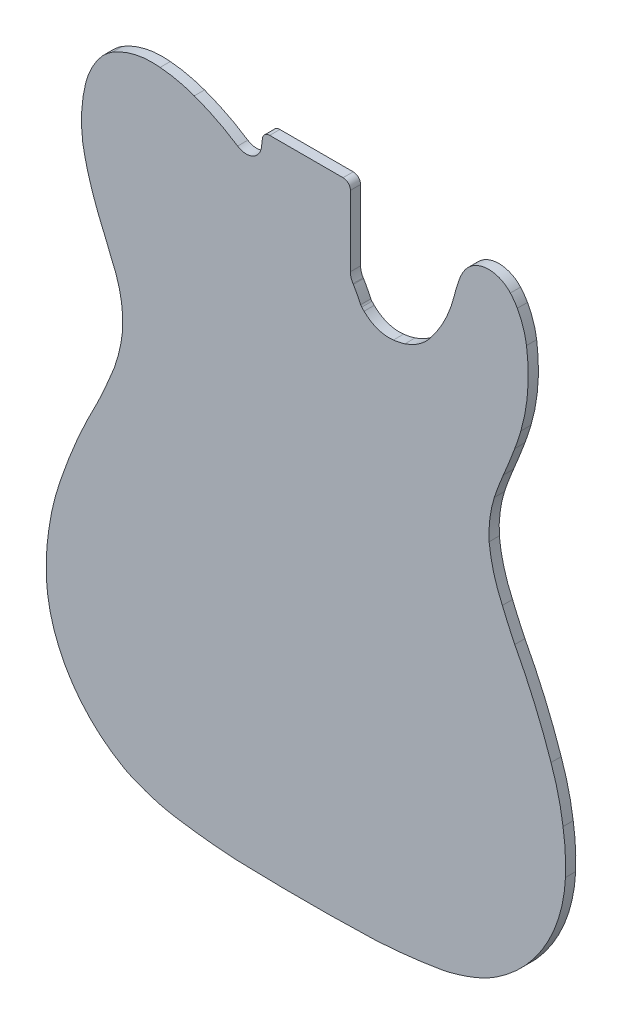
SolidWorks part; units mm, degrees
ref_plane "Front Plane" through (0, 0, 0) normal (0, 0, 1) x (1, 0, 0)
ref_plane "Top Plane" through (0, 0, 0) normal (0, 1, 0) x (1, 0, 0)
ref_plane "Right Plane" through (0, 0, 0) normal (1, 0, 0) x (0, 0, -1)
sketch "Sketch1" plane through (0, 0, 0) normal (0, 0, 1) x (1, 0, 0)
  line L0 (255.3675, -212.0656) -> (264.4462, -212.0656) construction
  line L1 (264.4462, -212.0656) -> (273.5248, -212.0656) construction
  line L2 (254.4921, -211.9425) -> (229.09, -204.656) construction
  line L3 (274.4003, -211.9425) -> (299.8024, -204.656) construction
  line L4 (264.4462, -197.0288) -> (264.4462, -188.6259) construction
  line L5 (292.1992, -149.0184) -> (292.1992, -105.0808)
  line L6 (353.0408, -434.0524) -> (359.3908, -434.0524) construction
  line L7 (354.3108, -292.5744) -> (358.1208, -292.5744) construction
  line L8 (368.9158, -303.3694) -> (368.9158, -424.5274) construction
  line L9 (343.5158, -303.3694) -> (343.5158, -424.5274) construction
  line L10 (231.3871, -188.3166) -> (257.385, -188.3166) construction
  line L11 (271.5074, -188.3166) -> (297.5053, -188.3166) construction
  line L12 (292.2083, -154.6088) -> (292.4425, -170.3149) construction
  line L13 (237.3236, -111.7284) -> (236.4498, -170.3149) construction
  line L14 (261.2712, -222.8223) -> (261.2712, -212.0656) construction
  line L15 (267.6212, -222.5163) -> (267.6212, -212.0656) construction
  line L16 (355.5808, -417.0887) -> (440.1841, -462.3756)
  line L17 (170.139, -116.9111) -> (172.2398, -80.4263) construction
  line L26 (233.0908, -326.0407) -> (228.0254, -311.007) construction
  line L27 (280.249, -340.996) -> (237.8411, -330.4226) construction
  line L28 (286.5004, -339.3572) -> (298.0308, -328.4613) construction
  line L29 (271.5011, -294.9508) -> (296.5271, -311.3952) construction
  line L30 (267.182, -293.874) -> (237.3652, -296.6444) construction
  line L31 (292.2083, -154.6088) -> (293.7952, -154.6089)
  line L32 (237.3236, -111.7284) -> (236.159, -111.7284)
  line L33 (264.4462, -533.3397) -> (264.4462, -35.9424) construction
  line L34 (264.446, -176.7596) -> (264.446, -168.3324) construction
  line L35 (242.7991, -176.7596) -> (257.385, -176.7596) construction
  line L36 (271.5074, -176.7596) -> (286.0933, -176.7596) construction
  line L37 (271.5074, -188.3166) -> (271.5074, -176.7596) construction
  line L38 (257.385, -188.3166) -> (257.385, -176.7596) construction
  line L39 (311.5028, -266.3979) -> (268.9363, -223.8315) construction
  line L40 (302.5225, -275.3781) -> (259.9561, -232.8117) construction
  line L41 (287.6272, -100.5088) -> (241.8598, -100.5088)
  line L42 (236.7013, -109.5293) -> (237.3226, -104.5183)
  line L45 (368.9158, -411.6223) -> (420.0889, -439.0145)
  line L46 (362.6504, -433.4773) -> (409.7247, -458.6755)
  line L47 (300.9797, -323.698) -> (343.5158, -323.698) construction
  line L48 (300.9797, -317.348) -> (343.5158, -317.348) construction
  line L49 (343.5158, -311.8813) -> (308.6561, -277.0216) construction
  line L50 (343.5158, -302.901) -> (313.1462, -272.5315) construction
  arc A0 (298.5861, -163.6364) -> (299.2711, -164.6283) centre (301.4937, -162.3609) ccw
  arc A1 (300.7364, -166.0922) -> (299.2711, -164.6283) centre (222.8934, -242.5472) ccw
  arc A2 (300.7364, -166.0922) -> (319.0259, -172.5122) centre (316.4123, -150.6962) ccw
  arc A3 (319.0259, -172.5122) -> (326.2352, -170.944) centre (314.4164, -133.9661) ccw
  arc A4 (326.2352, -170.944) -> (341.6924, -160.3725) centre (316.2829, -139.806) ccw
  arc A5 (341.6924, -160.3725) -> (356.9315, -129.8398) centre (280.2373, -110.6305) ccw
  arc A6 (360.2177, -118.9602) -> (356.9315, -129.8398) centre (472.2447, -158.7341) ccw
  arc A7 (363.6913, -112.2691) -> (360.2177, -118.9602) centre (386.4375, -128.3247) ccw
  arc A8 (392.0008, -110.6336) -> (363.6913, -112.2691) centre (378.4982, -122.7399) ccw
  arc A9 (396.3203, -116.7099) -> (392.0008, -110.6336) centre (367.666, -132.5065) ccw
  arc A10 (402.0691, -133.9701) -> (396.3203, -116.7099) centre (352.5181, -140.8862) ccw
  arc A11 (398.5108, -181.9349) -> (402.0691, -133.9701) centre (289.2584, -149.7157) ccw
  arc A12 (394.7117, -193.3187) -> (398.5108, -181.9349) centre (237.0194, -134.3662) ccw
  arc A13 (387.6043, -211.1738) -> (394.7117, -193.3187) centre (-23.048, -37.3677) ccw
  arc A14 (387.6043, -211.1738) -> (381.9731, -226.053) centre (577.8696, -291.6876) ccw
  circle A15 centre (378.0352, -293.8788) radius 0.889
  arc A33 (368.9158, -303.3694) -> (358.1208, -292.5744) centre (358.1208, -303.3694) ccw construction
  arc A34 (354.3108, -292.5744) -> (343.5158, -303.3694) centre (354.3108, -303.3694) ccw construction
  arc A35 (231.3871, -188.3166) -> (229.09, -204.656) centre (231.3871, -196.6478) ccw construction
  arc A36 (299.8024, -204.656) -> (297.5053, -188.3166) centre (297.5053, -196.6478) ccw construction
  arc A37 (273.5248, -212.0656) -> (274.4003, -211.9425) centre (273.5248, -208.8906) ccw construction
  arc A38 (254.4921, -211.9425) -> (255.3675, -212.0656) centre (255.3675, -208.8906) ccw construction
  circle A39 centre (300.6412, -197.0288) radius 2.3813 construction
  circle A40 centre (228.2512, -197.0288) radius 2.3813 construction
  circle A41 centre (190.7346, -293.8788) radius 0.889
  circle A45 centre (216.6438, -195.7754) radius 0.9906 construction
  circle A46 centre (237.8426, -363.958) radius 0.9906 construction
  arc A47 (369.9797, -491.4239) -> (383.1407, -484.5884) centre (341.6053, -420.7038) ccw
  arc A48 (383.1407, -484.5884) -> (426.3677, -409.2054) centre (331.2197, -404.73) ccw
  circle A49 centre (361.0363, -437.4278) radius 0.9906 construction
  circle A50 centre (375.8404, -153.7439) radius 0.9906
  arc A51 (292.1992, -105.0808) -> (287.6272, -100.5088) centre (287.6272, -105.0808) ccw
  arc A52 (359.3908, -434.0524) -> (368.9158, -424.5274) centre (359.3908, -424.5274) ccw construction
  arc A53 (343.5158, -424.5274) -> (353.0408, -434.0524) centre (353.0408, -424.5274) ccw construction
  circle A55 centre (356.2158, -289.002) radius 0.8255 construction
  circle A56 centre (356.2158, -437.6248) radius 0.8255 construction
  circle A57 centre (264.4462, -249.0804) radius 1.5875 construction
  circle A58 centre (264.4462, -477.6804) radius 1.5875
  arc A59 (286.0933, -176.7596) -> (292.4425, -170.3149) centre (286.0933, -170.4096) ccw construction
  arc A60 (236.4498, -170.3149) -> (242.7991, -176.7596) centre (242.7991, -170.4096) ccw construction
  circle A61 centre (296.8434, -363.9576) radius 1.0795 construction
  circle A62 centre (275.2536, -363.9576) radius 1.0795 construction
  circle A63 centre (253.664, -363.9576) radius 1.0795 construction
  circle A64 centre (232.0734, -363.9576) radius 1.0795 construction
  circle A65 centre (291.4462, -372.0852) radius 1.651 construction
  circle A66 centre (280.6516, -372.0852) radius 1.651 construction
  circle A67 centre (269.8566, -372.0852) radius 1.651 construction
  circle A68 centre (259.061, -372.0852) radius 1.651 construction
  circle A69 centre (248.2654, -372.0852) radius 1.651 construction
  circle A70 centre (237.4714, -372.0852) radius 1.651 construction
  circle A91 centre (378.3902, -122.9872) radius 0.889
  circle A92 centre (324.0598, -293.8788) radius 0.889 construction
  circle A93 centre (228.8868, -140.5904) radius 0.889
  arc A94 (237.3652, -296.6444) -> (228.0254, -311.007) centre (238.3756, -307.5196) ccw construction
  arc A95 (233.0908, -326.0407) -> (237.8411, -330.4226) centre (239.4695, -323.8915) ccw construction
  arc A96 (280.249, -340.996) -> (286.5004, -339.3572) centre (281.8774, -334.465) ccw construction
  arc A97 (298.0308, -328.4613) -> (296.5271, -311.3952) centre (290.5293, -320.523) ccw construction
  arc A98 (271.5011, -294.9508) -> (267.182, -293.874) centre (267.8047, -300.5761) ccw construction
  arc A99 (268.9363, -223.8315) -> (259.9561, -232.8117) centre (264.4462, -228.3216) ccw construction
  arc A100 (302.5225, -275.3781) -> (311.5028, -275.3781) centre (307.0126, -270.888) ccw construction
  arc A101 (311.5028, -275.3781) -> (311.5028, -266.3979) centre (307.0126, -270.888) ccw construction
  circle A102 centre (245.3978, -160.8336) radius 2.032
  circle A103 centre (283.4978, -160.8336) radius 2.032
  circle A104 centre (283.4978, -110.0336) radius 2.032
  circle A105 centre (245.3978, -110.0336) radius 2.032
  arc A106 (241.8598, -100.5088) -> (237.3226, -104.5183) centre (241.8598, -105.0808) ccw
  arc A107 (292.1992, -149.0184) -> (293.7952, -154.6089) centre (302.5829, -149.077) ccw
  arc A108 (293.7952, -154.6089) -> (294.036, -154.9688) centre (302.7937, -148.8489) ccw
  arc A109 (298.5861, -163.6364) -> (294.036, -154.9688) centre (234.5218, -191.7393) ccw
  arc A110 (381.9731, -226.053) -> (378.7456, -251.638) centre (451.614, -247.8341) ccw
  arc A111 (378.7456, -251.638) -> (387.0056, -281.868) centre (473.536, -241.9811) ccw
  arc A112 (387.0056, -281.868) -> (394.746, -299.1376) centre (668.7935, -165.937) ccw
  arc A113 (417.3556, -351.5884) -> (394.746, -299.1376) centre (80.4909, -465.6996) ccw
  arc A114 (424.8464, -382.4484) -> (417.3556, -351.5884) centre (273.7558, -402.7844) ccw
  arc A115 (426.3677, -409.2054) -> (424.8464, -382.4484) centre (286.7086, -403.7238) ccw
  arc A116 (353.3461, -496.801) -> (369.9797, -491.4239) centre (322.6987, -373.581) ccw
  arc A117 (307.8756, -502.3376) -> (349.8373, -497.5433) centre (288.5477, -147.1431) ccw
  arc A118 (221.4182, -502.3513) -> (307.8756, -502.3376) centre (264.4456, 766.9622) ccw
  arc A119 (182.0911, -498.0608) -> (220.5936, -502.3144) centre (240.3434, -147.16) ccw
  arc A120 (155.5294, -490.0098) -> (168.8471, -494.9386) centre (206.2073, -373.5338) ccw
  arc A121 (102.5148, -408.988) -> (150.7976, -487.651) centre (197.6727, -404.73) ccw
  arc A122 (104.046, -382.4484) -> (102.5148, -408.988) centre (242.065, -403.7256) ccw
  arc A123 (111.5356, -351.5884) -> (104.046, -382.4484) centre (255.1378, -402.7788) ccw
  arc A124 (134.1464, -299.1376) -> (111.5356, -351.5884) centre (448.2456, -465.6404) ccw
  arc A125 (134.1464, -299.1376) -> (141.8856, -281.868) centre (-139.905, -165.9555) ccw
  arc A126 (141.8856, -281.868) -> (150.1456, -251.638) centre (55.4068, -241.9953) ccw
  arc A127 (150.1456, -251.638) -> (143.0364, -216.2088) centre (77.3673, -247.8137) ccw
  arc A128 (143.0364, -216.2088) -> (136.806, -200.9676) centre (-189.4378, -343.226) ccw
  arc A129 (129.8252, -181.788) -> (136.806, -200.9676) centre (324.3166, -121.8593) ccw
  arc A130 (125.2556, -162.9888) -> (129.8252, -181.788) centre (275.6939, -136.3761) ccw
  arc A131 (127.036, -129.7188) -> (125.2556, -162.9888) centre (213.3553, -151.0206) ccw
  arc A132 (137.4456, -109.7788) -> (127.036, -129.7188) centre (173.1607, -141.1109) ccw
  arc A133 (143.666, -104.698) -> (137.4456, -109.7788) centre (162.4404, -134.0314) ccw
  arc A134 (173.5156, -97.9688) -> (143.666, -104.698) centre (168.4714, -145.1623) ccw
  arc A135 (194.8464, -102.668) -> (173.5156, -97.9688) centre (166.5725, -180.2475) ccw
  arc A136 (221.848, -116.3068) -> (194.8464, -102.668) centre (151.4563, -222.118) ccw
  arc A137 (221.848, -116.3068) -> (236.7013, -109.5293) centre (227.1904, -108.3501) ccw
  arc A138 (220.5936, -502.3144) -> (221.4182, -502.3513) centre (222.709, -464.2732) ccw
  arc A139 (349.8373, -497.5433) -> (353.3461, -496.801) centre (341.0846, -447.503) ccw
  arc A143 (168.8471, -494.9386) -> (182.0911, -498.0608) centre (198.7298, -397.8325) ccw
  arc A144 (150.7976, -487.651) -> (155.5294, -490.0098) centre (175.7968, -443.4279) ccw
  circle A145 centre (237.4714, -372.0852) radius 4.064 construction
  circle A146 centre (248.2654, -372.0852) radius 4.064 construction
  circle A147 centre (259.061, -372.0852) radius 4.064 construction
  circle A148 centre (269.8566, -372.0852) radius 4.064 construction
  circle A149 centre (280.6516, -372.0852) radius 4.064 construction
  circle A150 centre (291.4462, -372.0852) radius 4.064 construction
  circle A151 centre (237.4714, -372.0852) radius 4.826 construction
  circle A152 centre (248.2654, -372.0852) radius 4.826 construction
  circle A153 centre (259.061, -372.0852) radius 4.826 construction
  circle A154 centre (269.8566, -372.0852) radius 4.826 construction
  circle A155 centre (280.6516, -372.0852) radius 4.826 construction
  circle A156 centre (291.4462, -372.0852) radius 4.826 construction
  circle A157 centre (232.0734, -363.9576) radius 2.032 construction
  circle A158 centre (253.664, -363.9576) radius 2.032 construction
  circle A159 centre (275.2536, -363.9576) radius 2.032 construction
  circle A160 centre (296.8434, -363.9576) radius 2.032 construction
sketch "Sketch2" plane through (0, 0, 0) normal (0, 0, 1) x (1, 0, 0)
  line L0 (236.7013, -109.5293) -> (237.3226, -104.5183) construction
  line L1 (287.6272, -100.5088) -> (241.8598, -100.5088) construction
  line L2 (292.1992, -149.0184) -> (292.1992, -105.0808) construction
  line L3 (236.7013, -109.5293) -> (237.3226, -104.5183)
  line L4 (287.6272, -100.5088) -> (241.8598, -100.5088)
  line L5 (292.1992, -149.0184) -> (292.1992, -105.0808)
  arc A0 (293.7952, -154.6089) -> (294.036, -154.9688) centre (302.7937, -148.8489) ccw construction
  arc A1 (298.5861, -163.6364) -> (294.036, -154.9688) centre (234.5218, -191.7393) ccw construction
  arc A2 (298.5861, -163.6364) -> (299.2711, -164.6283) centre (301.4937, -162.3609) ccw construction
  arc A3 (300.7364, -166.0922) -> (299.2711, -164.6283) centre (222.8934, -242.5472) ccw construction
  arc A4 (300.7364, -166.0922) -> (319.0259, -172.5122) centre (316.4123, -150.6962) ccw construction
  arc A5 (319.0259, -172.5122) -> (326.2352, -170.944) centre (314.4164, -133.9661) ccw construction
  arc A6 (326.2352, -170.944) -> (341.6924, -160.3725) centre (316.2829, -139.806) ccw construction
  arc A7 (341.6924, -160.3725) -> (356.9315, -129.8398) centre (280.2373, -110.6305) ccw construction
  arc A8 (360.2177, -118.9602) -> (356.9315, -129.8398) centre (472.2447, -158.7341) ccw construction
  arc A9 (363.6913, -112.2691) -> (360.2177, -118.9602) centre (386.4375, -128.3247) ccw construction
  arc A10 (392.0008, -110.6336) -> (363.6913, -112.2691) centre (378.4982, -122.7399) ccw construction
  arc A11 (396.3203, -116.7099) -> (392.0008, -110.6336) centre (367.666, -132.5065) ccw construction
  arc A12 (402.0691, -133.9701) -> (396.3203, -116.7099) centre (352.5181, -140.8862) ccw construction
  arc A13 (398.5108, -181.9349) -> (402.0691, -133.9701) centre (289.2584, -149.7157) ccw construction
  arc A14 (394.7117, -193.3187) -> (398.5108, -181.9349) centre (237.0194, -134.3662) ccw construction
  arc A15 (387.6043, -211.1738) -> (394.7117, -193.3187) centre (-23.048, -37.3677) ccw construction
  arc A16 (387.6043, -211.1738) -> (381.9731, -226.053) centre (577.8696, -291.6876) ccw construction
  arc A17 (381.9731, -226.053) -> (378.7456, -251.638) centre (451.614, -247.8341) ccw construction
  arc A18 (378.7456, -251.638) -> (387.0056, -281.868) centre (473.536, -241.9811) ccw construction
  arc A19 (387.0056, -281.868) -> (394.746, -299.1376) centre (668.7935, -165.937) ccw construction
  arc A20 (417.3556, -351.5884) -> (394.746, -299.1376) centre (80.4909, -465.6996) ccw construction
  arc A21 (424.8464, -382.4484) -> (417.3556, -351.5884) centre (273.7558, -402.7844) ccw construction
  arc A22 (426.3677, -409.2054) -> (424.8464, -382.4484) centre (286.7086, -403.7238) ccw construction
  arc A23 (383.1407, -484.5884) -> (426.3677, -409.2054) centre (331.2197, -404.73) ccw construction
  arc A24 (369.9797, -491.4239) -> (383.1407, -484.5884) centre (341.6053, -420.7038) ccw construction
  arc A25 (353.3461, -496.801) -> (369.9797, -491.4239) centre (322.6987, -373.581) ccw construction
  arc A26 (349.8373, -497.5433) -> (353.3461, -496.801) centre (341.0846, -447.503) ccw construction
  arc A27 (307.8756, -502.3376) -> (349.8373, -497.5433) centre (288.5477, -147.1431) ccw construction
  arc A28 (221.4182, -502.3513) -> (307.8756, -502.3376) centre (264.4456, 766.9622) ccw construction
  arc A29 (220.5936, -502.3144) -> (221.4182, -502.3513) centre (222.709, -464.2732) ccw construction
  arc A30 (182.0911, -498.0608) -> (220.5936, -502.3144) centre (240.3434, -147.16) ccw construction
  arc A31 (168.8471, -494.9386) -> (182.0911, -498.0608) centre (198.7298, -397.8325) ccw construction
  arc A32 (155.5294, -490.0098) -> (168.8471, -494.9386) centre (206.2073, -373.5338) ccw construction
  arc A33 (150.7976, -487.651) -> (155.5294, -490.0098) centre (175.7968, -443.4279) ccw construction
  arc A34 (102.5148, -408.988) -> (150.7976, -487.651) centre (197.6727, -404.73) ccw construction
  arc A35 (104.046, -382.4484) -> (102.5148, -408.988) centre (242.065, -403.7256) ccw construction
  arc A36 (111.5356, -351.5884) -> (104.046, -382.4484) centre (255.1378, -402.7788) ccw construction
  arc A37 (134.1464, -299.1376) -> (111.5356, -351.5884) centre (448.2456, -465.6404) ccw construction
  arc A38 (134.1464, -299.1376) -> (141.8856, -281.868) centre (-139.905, -165.9555) ccw construction
  arc A39 (141.8856, -281.868) -> (150.1456, -251.638) centre (55.4068, -241.9953) ccw construction
  arc A40 (150.1456, -251.638) -> (143.0364, -216.2088) centre (77.3673, -247.8137) ccw construction
  arc A41 (143.0364, -216.2088) -> (136.806, -200.9676) centre (-189.4378, -343.226) ccw construction
  arc A42 (129.8252, -181.788) -> (136.806, -200.9676) centre (324.3166, -121.8593) ccw construction
  arc A43 (125.2556, -162.9888) -> (129.8252, -181.788) centre (275.6939, -136.3761) ccw construction
  arc A44 (127.036, -129.7188) -> (125.2556, -162.9888) centre (213.3553, -151.0206) ccw construction
  arc A45 (137.4456, -109.7788) -> (127.036, -129.7188) centre (173.1607, -141.1109) ccw construction
  arc A46 (143.666, -104.698) -> (137.4456, -109.7788) centre (162.4404, -134.0314) ccw construction
  arc A47 (173.5156, -97.9688) -> (143.666, -104.698) centre (168.4714, -145.1623) ccw construction
  arc A48 (194.8464, -102.668) -> (173.5156, -97.9688) centre (166.5725, -180.2475) ccw construction
  arc A49 (221.848, -116.3068) -> (194.8464, -102.668) centre (151.4563, -222.118) ccw construction
  arc A50 (221.848, -116.3068) -> (236.7013, -109.5293) centre (227.1904, -108.3501) ccw construction
  arc A51 (241.8598, -100.5088) -> (237.3226, -104.5183) centre (241.8598, -105.0808) ccw construction
  arc A52 (292.1992, -105.0808) -> (287.6272, -100.5088) centre (287.6272, -105.0808) ccw construction
  arc A53 (292.1992, -149.0184) -> (293.7952, -154.6089) centre (302.5829, -149.077) ccw construction
  arc A54 (293.7952, -154.6089) -> (294.036, -154.9688) centre (302.7937, -148.8489) ccw
  arc A55 (298.5861, -163.6364) -> (294.036, -154.9688) centre (234.5218, -191.7393) ccw
  arc A56 (298.5861, -163.6364) -> (299.2711, -164.6283) centre (301.4937, -162.3609) ccw
  arc A57 (300.7364, -166.0922) -> (299.2711, -164.6283) centre (222.8934, -242.5472) ccw
  arc A58 (300.7364, -166.0922) -> (319.0259, -172.5122) centre (316.4123, -150.6962) ccw
  arc A59 (319.0259, -172.5122) -> (326.2352, -170.944) centre (314.4164, -133.9661) ccw
  arc A60 (326.2352, -170.944) -> (341.6924, -160.3725) centre (316.2829, -139.806) ccw
  arc A61 (341.6924, -160.3725) -> (356.9315, -129.8398) centre (280.2373, -110.6305) ccw
  arc A62 (360.2177, -118.9602) -> (356.9315, -129.8398) centre (472.2447, -158.7341) ccw
  arc A63 (363.6913, -112.2691) -> (360.2177, -118.9602) centre (386.4375, -128.3247) ccw
  arc A64 (392.0008, -110.6336) -> (363.6913, -112.2691) centre (378.4982, -122.7399) ccw
  arc A65 (396.3203, -116.7099) -> (392.0008, -110.6336) centre (367.666, -132.5065) ccw
  arc A66 (402.0691, -133.9701) -> (396.3203, -116.7099) centre (352.5181, -140.8862) ccw
  arc A67 (398.5108, -181.9349) -> (402.0691, -133.9701) centre (289.2584, -149.7157) ccw
  arc A68 (394.7117, -193.3187) -> (398.5108, -181.9349) centre (237.0194, -134.3662) ccw
  arc A69 (387.6043, -211.1738) -> (394.7117, -193.3187) centre (-23.048, -37.3677) ccw
  arc A70 (387.6043, -211.1738) -> (381.9731, -226.053) centre (577.8696, -291.6876) ccw
  arc A71 (381.9731, -226.053) -> (378.7456, -251.638) centre (451.614, -247.8341) ccw
  arc A72 (378.7456, -251.638) -> (387.0056, -281.868) centre (473.536, -241.9811) ccw
  arc A73 (387.0056, -281.868) -> (394.746, -299.1376) centre (668.7935, -165.937) ccw
  arc A74 (417.3556, -351.5884) -> (394.746, -299.1376) centre (80.4909, -465.6996) ccw
  arc A75 (424.8464, -382.4484) -> (417.3556, -351.5884) centre (273.7558, -402.7844) ccw
  arc A76 (426.3677, -409.2054) -> (424.8464, -382.4484) centre (286.7086, -403.7238) ccw
  arc A77 (383.1407, -484.5884) -> (426.3677, -409.2054) centre (331.2197, -404.73) ccw
  arc A78 (369.9797, -491.4239) -> (383.1407, -484.5884) centre (341.6053, -420.7038) ccw
  arc A79 (353.3461, -496.801) -> (369.9797, -491.4239) centre (322.6987, -373.581) ccw
  arc A80 (349.8373, -497.5433) -> (353.3461, -496.801) centre (341.0846, -447.503) ccw
  arc A81 (307.8756, -502.3376) -> (349.8373, -497.5433) centre (288.5477, -147.1431) ccw
  arc A82 (221.4182, -502.3513) -> (307.8756, -502.3376) centre (264.4456, 766.9622) ccw
  arc A83 (220.5936, -502.3144) -> (221.4182, -502.3513) centre (222.709, -464.2732) ccw
  arc A84 (182.0911, -498.0608) -> (220.5936, -502.3144) centre (240.3434, -147.16) ccw
  arc A85 (168.8471, -494.9386) -> (182.0911, -498.0608) centre (198.7298, -397.8325) ccw
  arc A86 (155.5294, -490.0098) -> (168.8471, -494.9386) centre (206.2073, -373.5338) ccw
  arc A87 (150.7976, -487.651) -> (155.5294, -490.0098) centre (175.7968, -443.4279) ccw
  arc A88 (102.5148, -408.988) -> (150.7976, -487.651) centre (197.6727, -404.73) ccw
  arc A89 (104.046, -382.4484) -> (102.5148, -408.988) centre (242.065, -403.7256) ccw
  arc A90 (111.5356, -351.5884) -> (104.046, -382.4484) centre (255.1378, -402.7788) ccw
  arc A91 (134.1464, -299.1376) -> (111.5356, -351.5884) centre (448.2456, -465.6404) ccw
  arc A92 (134.1464, -299.1376) -> (141.8856, -281.868) centre (-139.905, -165.9555) ccw
  arc A93 (141.8856, -281.868) -> (150.1456, -251.638) centre (55.4068, -241.9953) ccw
  arc A94 (150.1456, -251.638) -> (143.0364, -216.2088) centre (77.3673, -247.8137) ccw
  arc A95 (143.0364, -216.2088) -> (136.806, -200.9676) centre (-189.4378, -343.226) ccw
  arc A96 (129.8252, -181.788) -> (136.806, -200.9676) centre (324.3166, -121.8593) ccw
  arc A97 (125.2556, -162.9888) -> (129.8252, -181.788) centre (275.6939, -136.3761) ccw
  arc A98 (127.036, -129.7188) -> (125.2556, -162.9888) centre (213.3553, -151.0206) ccw
  arc A99 (137.4456, -109.7788) -> (127.036, -129.7188) centre (173.1607, -141.1109) ccw
  arc A100 (143.666, -104.698) -> (137.4456, -109.7788) centre (162.4404, -134.0314) ccw
  arc A101 (173.5156, -97.9688) -> (143.666, -104.698) centre (168.4714, -145.1623) ccw
  arc A102 (194.8464, -102.668) -> (173.5156, -97.9688) centre (166.5725, -180.2475) ccw
  arc A103 (221.848, -116.3068) -> (194.8464, -102.668) centre (151.4563, -222.118) ccw
  arc A104 (221.848, -116.3068) -> (236.7013, -109.5293) centre (227.1904, -108.3501) ccw
  arc A105 (241.8598, -100.5088) -> (237.3226, -104.5183) centre (241.8598, -105.0808) ccw
  arc A106 (292.1992, -105.0808) -> (287.6272, -100.5088) centre (287.6272, -105.0808) ccw
  arc A107 (292.1992, -149.0184) -> (293.7952, -154.6089) centre (302.5829, -149.077) ccw
extrude "Extrude1" add sketch "Sketch2" along normal blind 44.45
sketch "Sketch8" plane through (0, 0, 0) normal (0, 0, -1) x (-1, 0, 0)
  line L1 (-666.8895, -10.4649) -> (153.4061, -10.4649)
  line L2 (-666.8895, -10.4649) -> (-666.8895, -620.2918)
  line L3 (-666.8895, -620.2918) -> (153.4061, -620.2918)
  line L4 (153.4061, -10.4649) -> (153.4061, -620.2918)
extrude "Cut-Extrude1" cut sketch "Sketch8" against normal blind 38.1
